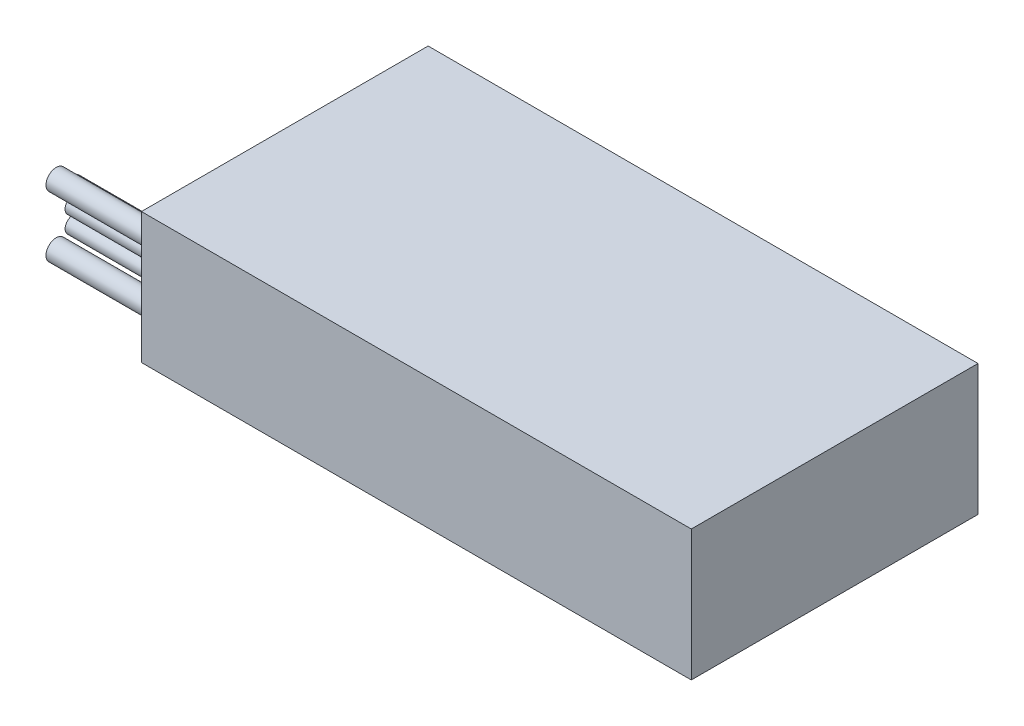
SolidWorks part; units mm, degrees
ref_plane "Front Plane" through (0, 0, 0) normal (0, 0, 1) x (1, 0, 0)
ref_plane "Top Plane" through (0, 0, 0) normal (0, 1, 0) x (1, 0, 0)
ref_plane "Right Plane" through (0, 0, 0) normal (1, 0, 0) x (0, 0, -1)
sketch "Sketch1" plane through (0, 0, 0) normal (0, 0, 1) x (1, 0, 0)
  line L1 (0, 0) -> (67.7, 0)
  line L2 (0, 0) -> (0, 16.1)
  line L3 (0, 16.1) -> (67.7, 16.1)
  line L4 (67.7, 0) -> (67.7, 16.1)
  dimension "D1" = 67.7
  dimension "D2" = 16.1
extrude "Boss-Extrude1" add sketch "Sketch1" along normal blind 35.3
sketch "Sketch3" plane through (0, 0, 0) normal (-1, 0, 0) x (0, 0, 1)
  line L0 (32.8, 11.8) -> (32.8, 4.3) construction
  line L1 (30.7, 8.05) -> (32.8, 8.05) construction
  line L2 (30.7, 5.95) -> (30.7, 8.05) construction
  line L3 (30.7, 8.05) -> (30.7, 10.15) construction
  line L4 (32.8, 8.05) -> (35.3, 8.05) construction
  line L5 (35.3, 16.1) -> (35.3, 0) construction
  circle A0 centre (30.7, 10.15) radius 1
  circle A1 centre (30.7, 8.05) radius 1
  circle A2 centre (30.7, 5.95) radius 1
  circle A3 centre (32.8, 4.3) radius 1.25
  circle A4 centre (32.8, 11.8) radius 1.25
  dimension "D3" = 2
  dimension "D4" = 2.5
  dimension "D1" = 2.1
  dimension "D2" = 7.5
  dimension "D5" = 2.5
  dimension "D6" = 2.1
extrude "Boss-Extrude2" add sketch "Sketch3" along normal blind 13
